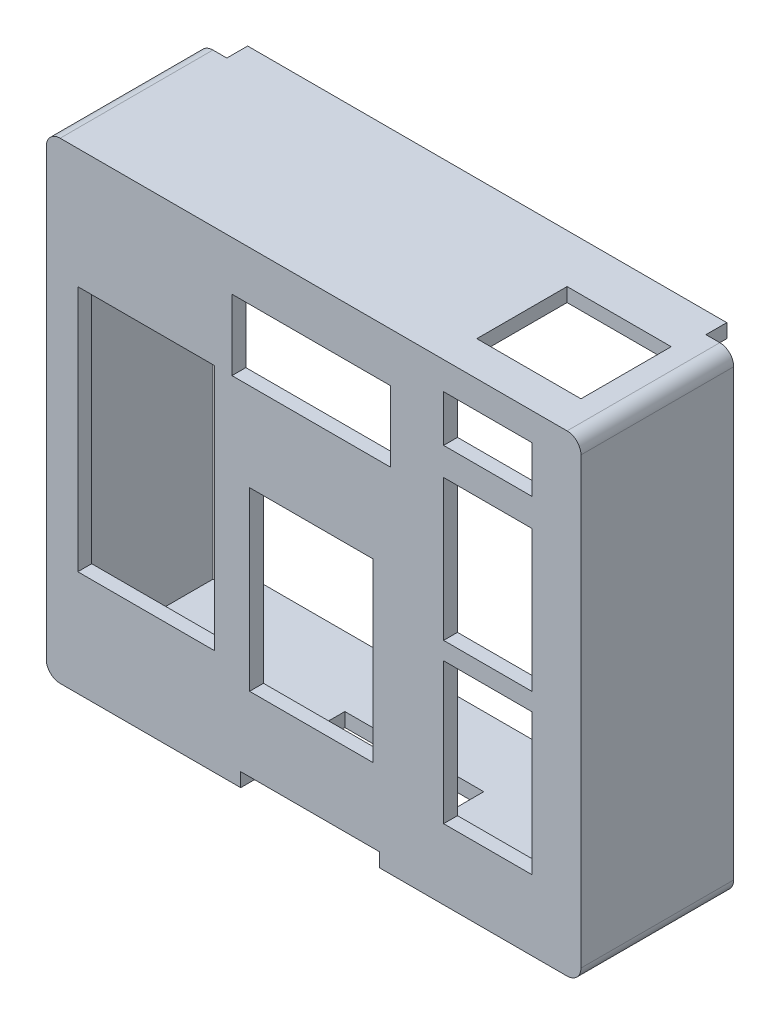
SolidWorks part; units mm, degrees
ref_plane "前视基准面" through (0, 0, 0) normal (0, 0, 1) x (1, 0, 0)
ref_plane "上视基准面" through (0, 0, 0) normal (0, 1, 0) x (1, 0, 0)
ref_plane "右视基准面" through (0, 0, 0) normal (1, 0, 0) x (0, 0, -1)
sketch "草图1" plane through (0, 0, 0) normal (0, 0, 1) x (1, 0, 0)
  line L1 (0, 0) -> (73, 0)
  line L2 (0, 0) -> (0, -64)
  line L3 (0, -64) -> (73, -64)
  line L4 (73, 0) -> (73, -64)
  line L5 (24.74, -15.24) -> (47.6, -15.24)
  line L6 (24.74, -15.24) -> (24.74, -5.08)
  line L7 (24.74, -5.08) -> (47.6, -5.08)
  line L8 (47.6, -15.24) -> (47.6, -5.08)
  line L9 (55.22, -12.7) -> (67.92, -12.7)
  line L10 (55.22, -12.7) -> (55.22, -33.02)
  line L11 (55.22, -33.02) -> (67.92, -33.02)
  line L12 (67.92, -12.7) -> (67.92, -33.02)
  line L13 (55.22, -35.56) -> (67.92, -35.56)
  line L14 (55.22, -35.56) -> (55.22, -55.88)
  line L15 (55.22, -55.88) -> (67.92, -55.88)
  line L16 (67.92, -35.56) -> (67.92, -55.88)
  line L17 (2.54, -15.24) -> (22.2, -15.24)
  line L18 (2.54, -15.24) -> (2.54, -50.8)
  line L19 (2.54, -50.8) -> (22.2, -50.8)
  line L20 (22.2, -15.24) -> (22.2, -50.8)
  line L21 (27.28, -27.94) -> (45.06, -27.94)
  line L22 (27.28, -27.94) -> (27.28, -53.34)
  line L23 (27.28, -53.34) -> (45.06, -53.34)
  line L24 (45.06, -27.94) -> (45.06, -53.34)
  point P25 (0, -32)
  point P26 (44.6933, -53.34)
  dimension "D1" = 64
  dimension "D2" = 73
  dimension "D3" = 22.86
  dimension "D4" = 10.16
  dimension "D5" = 12.7
  dimension "D6" = 12.7
  dimension "D7" = 20.32
  dimension "D8" = 20.32
  dimension "D9" = 2.54
  dimension "D10" = 0
  dimension "D11" = 12.7
  dimension "D12" = 7.62
  dimension "D13" = 25.4
  dimension "D14" = 5.08
  dimension "D15" = 2.54
  dimension "D16" = 12.7
  dimension "D17" = 25.4
  dimension "D18" = 2.54
  dimension "D19" = 2.54
  dimension "D20" = 35.56
  dimension "D21" = 15.24
  dimension "D22" = 2.54
extrude "凸台-拉伸1" add sketch "草图1" along normal blind 2
sketch "草图2" plane through (0, 0, 2) normal (0, 0, 1) x (1, 0, 0)
  line L0 (75, 2) -> (75, -66)
  line L1 (73, 0) -> (0, 0)
  line L2 (73, 0) -> (73, -64)
  line L3 (73, -64) -> (0, -64)
  line L4 (0, 0) -> (0, -64)
  line L5 (75, -66) -> (-2, -66)
  line L6 (-2, 2) -> (-2, -66)
  line L7 (75, 2) -> (-2, 2)
  dimension "D1" = 2
extrude "凸台-拉伸2" add sketch "草图2" against normal blind 25
fillet "圆角1" radius 2 4 edges at (75, -66, -10.5) (-2, -66, -10.5) (-2, 2, -10.5) (75, 2, -10.5)
sketch "草图5" plane through (75, 0, 0) normal (1, 0, 0) x (0, 0, -1)
  line L1 (23, -66) -> (-2, -66) construction
  line L2 (23, 2) -> (20, 2)
  line L3 (23, 2) -> (23, -66)
  line L4 (23, -66) -> (20, -66)
  line L7 (20, 2) -> (20, -66)
  dimension "D1" = 3
extrude "切除-拉伸1" cut sketch "草图5" against normal blind 4
sketch "草图7" plane through (0, 0, 0) normal (1, 0, 0) x (0, 0, -1)
  line L1 (20, -66) -> (23, -66)
  line L2 (20, -66) -> (20, 2)
  line L3 (20, 2) -> (23, 2)
  line L4 (23, -66) -> (23, 2)
extrude "切除-拉伸2" cut sketch "草图7" against normal blind 2 and the other way blind 2
sketch "草图8" plane through (0, -66, 0) normal (0, -1, 0) x (1, 0, 0)
  line L0 (0, 2) -> (73, 2) construction
  line L1 (46, 2) -> (26, 2)
  line L2 (46, 2) -> (46, -13)
  line L3 (46, -13) -> (26, -13)
  line L4 (26, 2) -> (26, -13)
  line L5 (-2, -20) -> (-2, 2) construction
  point P8 (-2, -9)
  dimension "D1" = 15
  dimension "D2" = 0
  dimension "D3" = 20
  dimension "D4" = 28
extrude "切除-拉伸3" cut sketch "草图8" against normal blind 2
sketch "草图9" plane through (0, 2, 0) normal (0, 1, 0) x (1, 0, 0)
  line L0 (73, -2) -> (0, -2) construction
  line L1 (70, 3) -> (55, 3)
  line L2 (70, 3) -> (70, 16)
  line L3 (70, 16) -> (55, 16)
  line L4 (55, 3) -> (55, 16)
  line L5 (75, 20) -> (75, -2) construction
  line L6 (71, 20) -> (73, 20) construction
  dimension "D1" = 5
  dimension "D2" = 5
  dimension "D3" = 4
  dimension "D4" = 15
extrude "切除-拉伸4" cut sketch "草图9" against normal blind 2
sketch "草图10" plane through (0, 0, 2) normal (0, 0, 1) x (1, 0, 0)
  line L0 (55.22, -12.7) -> (55.22, -33.02) construction
  line L1 (55.22, -2) -> (67.92, -2)
  line L2 (55.22, -2) -> (55.22, -8.7)
  line L3 (55.22, -8.7) -> (67.92, -8.7)
  line L4 (67.92, -2) -> (67.92, -8.7)
  line L5 (67.92, -33.02) -> (67.92, -12.7) construction
  line L6 (67.92, -12.7) -> (55.22, -12.7) construction
  line L7 (73, 2) -> (0, 2) construction
  dimension "D1" = 0
  dimension "D2" = 0
  dimension "D3" = 4
  dimension "D4" = 4
extrude "切除-拉伸5" cut sketch "草图10" against normal blind 2
sketch "草图12" plane through (0, 0, 0) normal (0, 0, -1) x (-1, 0, 0)
  line L0 (0, -64) -> (-26, -64) construction
  line L1 (0, 0) -> (0, -64) construction
  line L2 (-1.5, -64) -> (0, -64)
  line L3 (0, -64) -> (0, -62.5)
  line L4 (-36.5, -66) -> (-36.5, 2) construction
  line L7 (0, -32) -> (-73, -32) construction
  line L8 (-73, -64) -> (-73, 0) construction
  line L9 (-2, -66) -> (-71, -66) construction
  line L10 (-71, 2) -> (-2, 2) construction
  line L11 (-73, -64) -> (-73, -62.5)
  line L12 (-71.5, -64) -> (-73, -64)
  line L13 (-71.5, 0) -> (-73, 0)
  line L14 (-73, 0) -> (-73, -1.5)
  line L15 (0, 0) -> (0, -1.5)
  line L16 (-1.5, 0) -> (0, 0)
  arc A0 (0, -62.5) -> (-1.5, -64) centre (-1.5, -62.5) ccw
  arc A1 (-73, -62.5) -> (-71.5, -64) centre (-71.5, -62.5) cw
  arc A2 (-73, -1.5) -> (-71.5, 0) centre (-71.5, -1.5) ccw
  arc A3 (0, -1.5) -> (-1.5, 0) centre (-1.5, -1.5) cw
  dimension "D1" = 1.5
extrude "凸台-拉伸3" add sketch "草图12" along normal blind 5
equation "\"25、\"=2"
